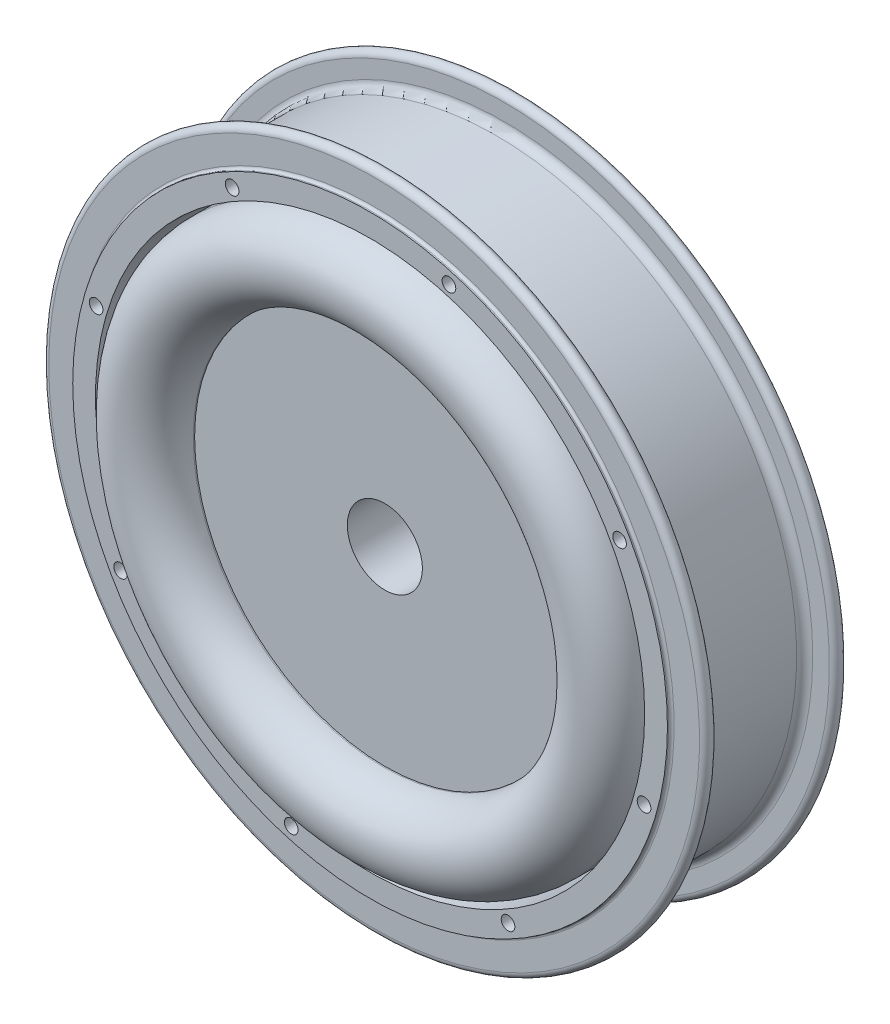
SolidWorks part; units mm, degrees
ref_plane "Front Plane" through (0, 0, 0) normal (0, 0, 1) x (1, 0, 0)
ref_plane "Top Plane" through (0, 0, 0) normal (0, 1, 0) x (1, 0, 0)
ref_plane "Right Plane" through (0, 0, 0) normal (1, 0, 0) x (0, 0, -1)
sketch "Sketch1" plane through (0, 0, 0) normal (0, 0, 1) x (1, 0, 0)
  circle A0 centre (0, 0) radius 102.5 construction
  circle A1 centre (0, 0) radius 102.5
  circle A2 centre (0, 0) radius 111 construction
  circle A3 centre (0, 0) radius 111
extrude "Boss-Extrude1" add sketch "Sketch1" along normal blind 56
sketch "Sketch2" plane through (0, 0, 56) normal (0, 0, 1) x (1, 0, 0)
  line L0 (0, 0) -> (29.4395, 102.2639) construction
  circle A0 centre (29.4395, 102.2639) radius 2.5447
extrude "Cut-Extrude1" cut sketch "Sketch2" against normal blind 15
pattern_circular "CirPattern1" count 8 over 360 about axis through (0, 0, 0) along (0, 0, 1) of "Cut-Extrude1"
sketch "Sketch3" plane through (0, 0, 56) normal (0, 0, 1) x (1, 0, 0)
  circle A0 centre (0, 0) radius 102.5 construction
  circle A1 centre (0, 0) radius 102.5
  circle A2 centre (0, 0) radius 151.5212
sketch "Sketch4" plane through (0, 0, 0) normal (0, 1, 0) x (1, 0, 0)
  line L0 (-111, -28) -> (0, -28) construction
  line L1 (-111, 0) -> (-111, -56) construction
  line L2 (0, -28) -> (0, 0) construction
  line L3 (0, 0) -> (0, -28) construction
  line L4 (-86, -5) -> (-86, -51) construction
  line L5 (-86, -5) -> (-86, -51) construction
  line L6 (-71, -5) -> (-71, -51)
  line L7 (-101, -5) -> (-101, -51)
  line L9 (111, 0) -> (-111, 0) construction
  line L10 (-151.5212, -56) -> (151.5212, -56) construction
  arc A0 (-71, -5) -> (-101, -5) centre (-86, -5) ccw
  arc A1 (-101, -51) -> (-71, -51) centre (-86, -51) ccw
  point P8 (-86, -28)
  point P13 (-86, 10)
  point P16 (-86, -66)
  dimension "D1" = 10
  dimension "D2" = 25
  dimension "D3" = 10
  dimension "D4" = 10
revolve "Revolve1" add sketch "Sketch4" angle 360 about L2
sketch "Sketch5" plane through (0, 0, 0) normal (0, 1, 0) x (1, 0, 0)
  line L0 (-71, -50.5) -> (-71, -15.5)
  line L1 (-71, -5) -> (-71, -51) construction
  line L2 (-71, -15.5) -> (-14, -15.5)
  line L3 (-14, -15.5) -> (-14, -50.5)
  line L4 (-14, -50.5) -> (-71, -50.5)
  line L5 (0, 0) -> (0, -87.1969) construction
  line L6 (102.5, 0) -> (-102.5, 0) construction
  line L7 (-102.5, -56) -> (102.5, -56) construction
  dimension "D1" = 28
  dimension "D2" = 15.5
  dimension "D3" = 5.5
  dimension "D4" = 35
revolve "Revolve2" add sketch "Sketch5" angle 360 about L5
sketch "Sketch6" plane through (0, 0, 0) normal (1, 0, 0) x (0, 0, -1)
  line L0 (-54.5, 112) -> (-54.5, 121.45)
  line L1 (0, 111) -> (-56, 111) construction
  line L2 (-50, 121.45) -> (-50, 115.2284)
  line L3 (-47, 112.2284) -> (-9, 112.2284)
  line L4 (-28, 111) -> (-28, 114.5264) construction
  line L5 (-56, 111) -> (-55.5, 111)
  line L6 (0, 111) -> (-0.5, 111)
  line L7 (-6, 121.45) -> (-6, 115.2284)
  line L8 (-1.5, 112) -> (-1.5, 121.45)
  line L9 (-56, 111) -> (-56, 110.7085)
  line L10 (-56, 111) -> (-56, -111) construction
  line L11 (-56, 110.7085) -> (0, 110.7085)
  line L12 (0, -111) -> (0, 111) construction
  line L13 (0, 110.7085) -> (0, 111)
  line L14 (0, 0) -> (-106.8076, 0) construction
  arc A0 (-54.5, 121.45) -> (-50, 121.45) centre (-52.25, 121.45) cw
  arc A1 (-54.5, 112) -> (-55.5, 111) centre (-55.5, 112) cw
  arc A2 (-50, 115.2284) -> (-47, 112.2284) centre (-47, 115.2284) ccw
  arc A3 (-6, 115.2284) -> (-9, 112.2284) centre (-9, 115.2284) cw
  arc A4 (-1.5, 112) -> (-0.5, 111) centre (-0.5, 112) ccw
  arc A5 (-1.5, 121.45) -> (-6, 121.45) centre (-3.75, 121.45) ccw
  point P6 (-52.25, 123.7)
  point P15 (-54.5, 111)
  point P18 (-50, 112.2284)
  point P29 (-28, 112.2284)
  dimension "D1" = 12.7
  dimension "D4" = 1
  dimension "D5" = 3
  dimension "D2" = 4.5
  dimension "D3" = 22
revolve "Revolve3" add sketch "Sketch6" angle 360 about L14
